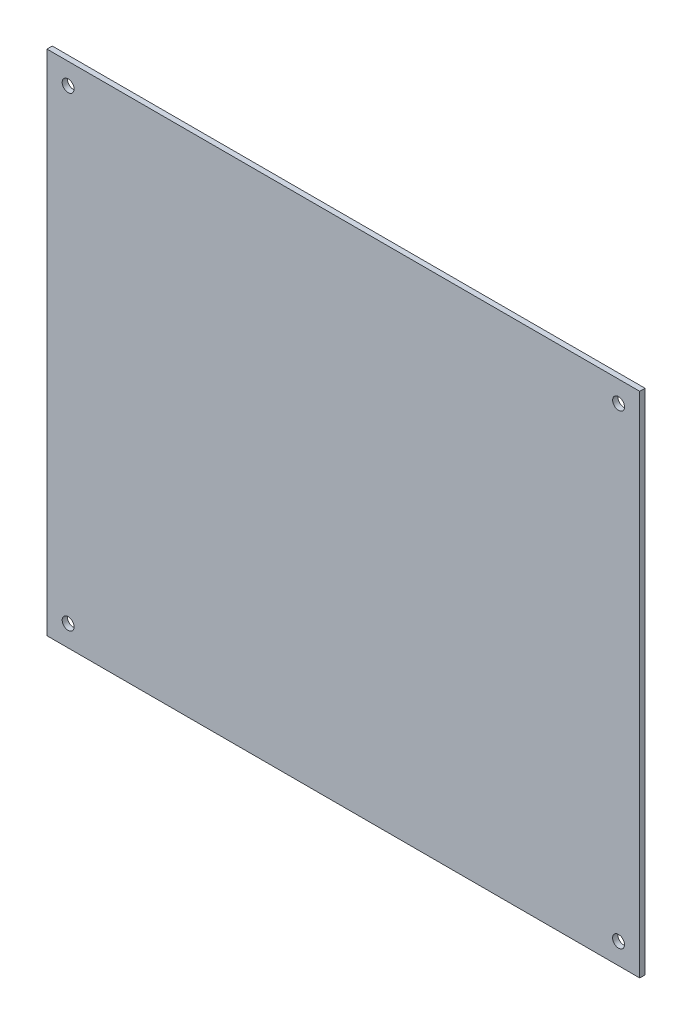
SolidWorks part; units mm, degrees
material "Acrylic (Medium-high impact)"
ref_plane "Front Plane" through (0, 0, 0) normal (0, 0, 1) x (1, 0, 0)
ref_plane "Top Plane" through (0, 0, 0) normal (0, 1, 0) x (1, 0, 0)
ref_plane "Right Plane" through (0, 0, 0) normal (1, 0, 0) x (0, 0, -1)
sketch "Sketch1" plane through (0, 0, 0) normal (0, 0, 1) x (1, 0, 0)
  line L1 (0, 0) -> (355.6, 0)
  line L2 (0, 0) -> (0, -304.8)
  line L3 (0, -304.8) -> (355.6, -304.8)
  line L4 (355.6, 0) -> (355.6, -304.8)
  dimension "D1" = 355.6
  dimension "D2" = 304.8
extrude "Boss-Extrude1" add sketch "Sketch1" along normal blind 3.175
sketch "Sketch2" plane through (0, 0, 3.175) normal (0, 0, 1) x (1, 0, 0)
  line L0 (177.8, 0) -> (177.8, -304.8) construction
  line L1 (355.6, 0) -> (0, 0) construction
  line L2 (0, -304.8) -> (355.6, -304.8) construction
  line L3 (0, -152.4) -> (355.6, -152.4) construction
  line L4 (0, 0) -> (0, -304.8) construction
  line L5 (355.6, -304.8) -> (355.6, 0) construction
  point P0 (12.7, -12.7)
  point P13 (342.9, -12.7)
  point P15 (342.9, -292.1)
  point P16 (12.7, -292.1)
  dimension "D1" = 12.7
  dimension "D2" = 12.7
hole_wizard "1/4 Clearance Hole1" positions "Sketch2" profile "Sketch3" hole size "1/4" standard "ANSI Inch" end condition up to next
sketch "Sketch3" plane through (12.7, -12.7, 3.175) normal (1, 0, 0) x (0, -1, 0)
  line L0 (0, 0) -> (0, 3.175)
  line L1 (0, 3.175) -> (3.5712, 3.175)
  line L2 (3.5712, 3.175) -> (3.5712, 0)
  line L5 (3.5712, 0) -> (0, 0)
  line L11 (0, -6.35) -> (0, 107.95) construction
  dimension "Thru Hole Dia." = 7.1425
  dimension "Thru Hole Depth" = 3.175
